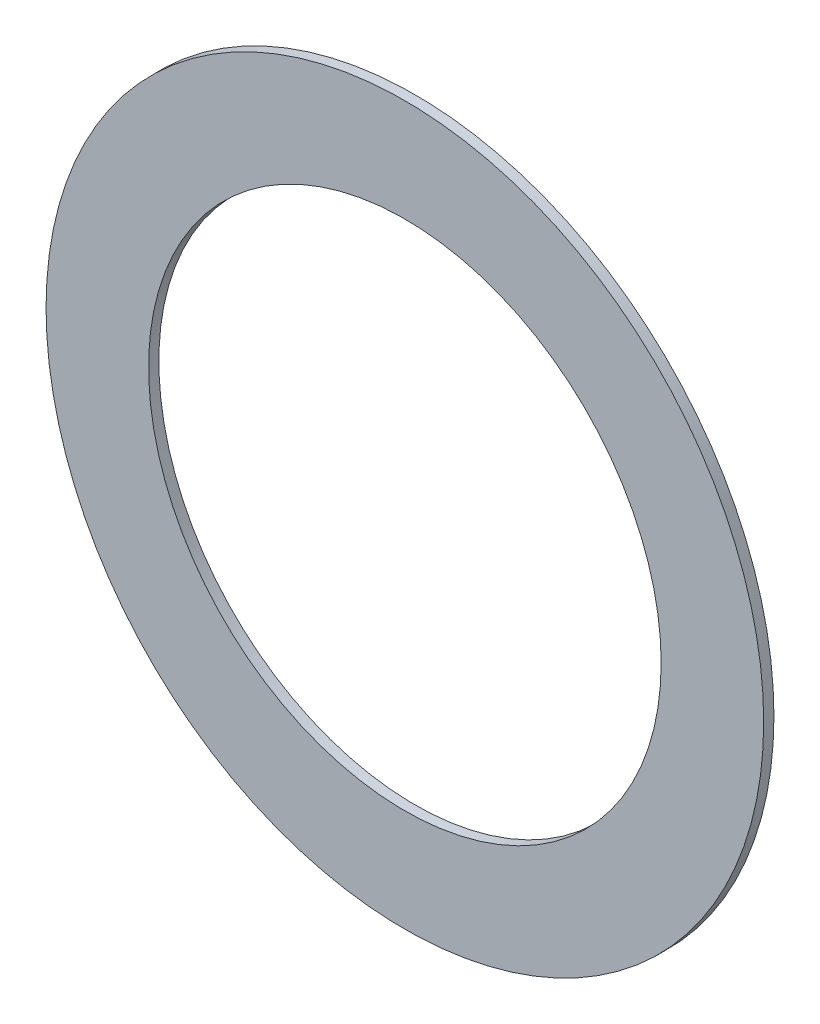
SolidWorks part; units mm, degrees
ref_plane "Front Plane" through (0, 0, 0) normal (0, 0, 1) x (1, 0, 0)
ref_plane "Top Plane" through (0, 0, 0) normal (0, 1, 0) x (1, 0, 0)
ref_plane "Right Plane" through (0, 0, 0) normal (1, 0, 0) x (0, 0, -1)
sketch "Sketch1" plane through (0, 0, 0) normal (0, 0, 1) x (1, 0, 0)
  circle A0 centre (0, 0) radius 25
  circle A1 centre (0, 0) radius 35
  dimension "D1" = 50
  dimension "D2" = 70
extrude "Boss-Extrude1" add sketch "Sketch1" along normal blind 1
